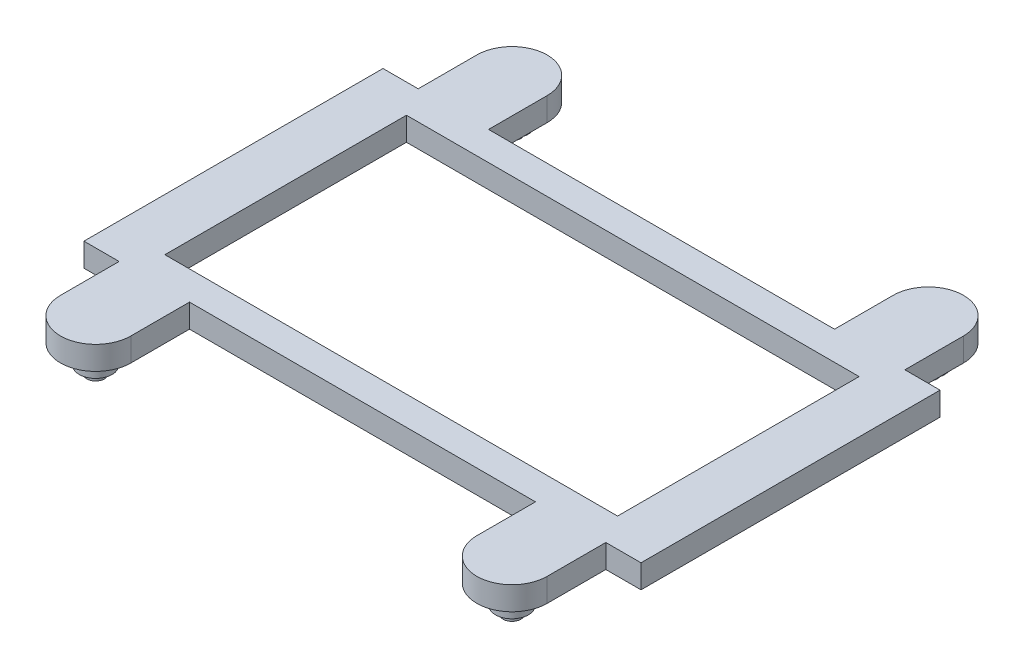
SolidWorks part; units mm, degrees
ref_plane "前视基准面" through (0, 0, 0) normal (0, 0, 1) x (1, 0, 0)
ref_plane "上视基准面" through (0, 0, 0) normal (0, 1, 0) x (1, 0, 0)
ref_plane "右视基准面" through (0, 0, 0) normal (1, 0, 0) x (0, 0, -1)
other "Configuration Table"
sketch "草图1" plane through (0, 0, 0) normal (0, 1, 0) x (1, 0, 0)
  line L0 (0, 35.4779) -> (0, -35.3561) construction
  line L1 (-47.5, 25.5) -> (-41.5, 25.5)
  line L2 (-47.5, 25.5) -> (-47.5, -25.5)
  line L3 (-47.5, -25.5) -> (-41.5, -25.5)
  line L4 (47.5, 25.5) -> (47.5, -25.5)
  line L5 (-47.5, 25.5) -> (47.5, -25.5) construction
  line L6 (-47.5, -25.5) -> (47.5, 25.5) construction
  line L9 (-41.5, 25.5) -> (-41.5, 35.5)
  line L11 (-29.5, 25.5) -> (-29.5, 35.5)
  line L12 (29.5, 25.5) -> (29.5, 35.5)
  line L14 (41.5, 25.5) -> (41.5, 35.5)
  line L15 (-78.7463, 0) -> (58.6748, 0) construction
  line L16 (41.5, -25.5) -> (41.5, -35.5)
  line L18 (29.5, -25.5) -> (29.5, -35.5)
  line L21 (-29.5, -25.5) -> (-29.5, -35.5)
  line L23 (-41.5, -25.5) -> (-41.5, -35.5)
  line L24 (-29.5, 25.5) -> (-3, 25.5)
  line L25 (41.5, 25.5) -> (47.5, 25.5)
  line L26 (41.5, -25.5) -> (47.5, -25.5)
  line L27 (-29.5, -25.5) -> (-3, -25.5)
  line L48 (3, 25.5) -> (29.5, 25.5)
  line L49 (3, -25.5) -> (29.5, -25.5)
  line L50 (-41.5, 35.5) -> (-29.5, 35.5) construction
  line L51 (-3, 25.5) -> (3, 25.5)
  line L52 (3, -25.5) -> (-3, -25.5)
  arc A16 (-29.5, 35.5) -> (-41.5, 35.5) centre (-35.5, 35.5) ccw
  arc A17 (29.5, 35.5) -> (41.5, 35.5) centre (35.5, 35.5) cw
  arc A18 (29.5, -35.5) -> (41.5, -35.5) centre (35.5, -35.5) ccw
  arc A19 (-29.5, -35.5) -> (-41.5, -35.5) centre (-35.5, -35.5) cw
  point P0 (0, 0)
  dimension "D10" = 71
  dimension "D1" = 95
  dimension "D3" = 83
  dimension "D4" = 12
  dimension "D5" = 10
extrude "凸台-拉伸1" add sketch "草图1" against normal blind 4
sketch "草图3" plane through (0, -4, 0) normal (0, -1, 0) x (1, 0, 0)
  line L0 (47.5, 25.5) -> (47.5, -25.5) construction
  line L1 (-45, -23) -> (45, -23)
  line L2 (-45, -23) -> (-45, 23)
  line L3 (-45, 23) -> (45, 23)
  line L4 (45, -23) -> (45, 23)
  line L5 (-45, -23) -> (45, 23) construction
  line L6 (-45, 23) -> (45, -23) construction
  line L7 (-29.5, 25.5) -> (29.5, 25.5) construction
  point P0 (0, 0)
  dimension "D1" = 2.5
  dimension "D2" = 2.5
sketch "草图4" plane through (0, -4, 0) normal (0, -1, 0) x (1, 0, 0)
  line L1 (-71.7869, 0) -> (71.1524, 0) construction
  line L2 (0, 61.1393) -> (0, -47.8922) construction
  circle A1 centre (35.5, 35.5) radius 2.8
  circle A2 centre (35.5, -35.5) radius 2.8
  circle A3 centre (-35.5, -35.5) radius 2.8
  circle A4 centre (-35.5, 35.5) radius 2.8
extrude "凸台-拉伸2" add sketch "草图4" along normal blind 3.3 separate body
sketch "草图5" plane through (0, -7.3, 0) normal (0, -1, 0) x (1, 0, 0)
  line L0 (-58.868, 0) -> (56.1189, 0) construction
  line L1 (0, 46.5823) -> (0, -51.4835) construction
  circle A0 centre (-35.5, 35.5) radius 1.5
  circle A1 centre (35.5, 35.5) radius 1.5
  circle A2 centre (35.5, -35.5) radius 1.5
  circle A3 centre (-35.5, -35.5) radius 1.5
extrude "凸台-拉伸3" add sketch "草图5" along normal blind 1.3 separate body
sketch "草图6" plane through (0, -4, 0) normal (0, -1, 0) x (1, 0, 0)
  line L0 (-29.5, 25.5) -> (29.5, 25.5) construction
  line L1 (-47.5, 25.5) -> (47.5, 25.5)
  line L2 (-47.5, 25.5) -> (-47.5, -25.5)
  line L3 (-47.5, -25.5) -> (47.5, -25.5)
  line L4 (47.5, 25.5) -> (47.5, -25.5)
  line L5 (29.5, -25.5) -> (-29.5, -25.5) construction
sketch "草图10" plane through (0, 0, 0) normal (0, 1, 0) x (1, 0, 0)
  line L5 (38.6, 20.6) -> (-38.6, 20.6)
  line L6 (38.6, 20.6) -> (38.6, -20.6)
  line L7 (38.6, -20.6) -> (-38.6, -20.6)
  line L8 (-38.6, 20.6) -> (-38.6, -20.6)
  line L9 (38.6, 20.6) -> (-38.6, -20.6) construction
  line L10 (38.6, -20.6) -> (-38.6, 20.6) construction
  point P0 (0, 0)
  dimension "D1" = 77.2
  dimension "D2" = 41.2
extrude "切除-拉伸5" cut sketch "草图10" against normal through all
sketch "草图16" plane through (0, 0, 0) normal (0, 1, 0) x (1, 0, 0)
  line L0 (-10, 23.05) -> (10, 23.05) construction
  line L1 (-10, 24.3) -> (10, 24.3)
  line L2 (-10, 21.8) -> (10, 21.8)
  line L3 (-1000, 0) -> (49000, 0) construction
  line L4 (0, -1000) -> (0, 49000) construction
  line L5 (29.5, 25.5) -> (-29.5, 25.5) construction
  line L6 (-10, -23.05) -> (10, -23.05) construction
  line L7 (-10, -24.3) -> (10, -24.3)
  line L8 (-10, -21.8) -> (10, -21.8)
  line L9 (38.6, 20.6) -> (-38.6, 20.6) construction
  arc A0 (-10, 24.3) -> (-10, 21.8) centre (-10, 23.05) ccw
  arc A1 (10, 21.8) -> (10, 24.3) centre (10, 23.05) ccw
  arc A2 (-10, -24.3) -> (-10, -21.8) centre (-10, -23.05) cw
  arc A3 (10, -21.8) -> (10, -24.3) centre (10, -23.05) cw
  circle A4 centre (19.07, 23.05) radius 1.6
  circle A5 centre (42.42, 23.05) radius 1.6
  circle A6 centre (-42.42, 23.05) radius 1.6
  circle A7 centre (-19.07, 23.05) radius 1.6
  circle A8 centre (42.42, -23.05) radius 1.6
  circle A9 centre (19.07, -23.05) radius 1.6
  circle A10 centre (-19.07, -23.05) radius 1.6
  circle A11 centre (-42.42, -23.05) radius 1.6
  point P2 (0, 23.05)
  point P17 (0, -23.05)
  point P27 (0, 23.05)
  dimension "D4" = 3.2
  dimension "D5" = 3.2
  dimension "D1" = 2.5
  dimension "D2" = 20
  dimension "D3" = 2.45
  dimension "D6" = 2.45
  dimension "D7" = 2.45
  dimension "D8" = 23.35
  dimension "D9" = 9.07
sketch "草图14" plane through (0, -3, 0) normal (0, -1, 0) x (1, 0, 0)
  line L0 (4.73, 0) -> (-4.73, 0) construction
  line L1 (-42, 24) -> (-37, 24)
  line L2 (-42, 24) -> (-42, 20)
  line L3 (-42, 20) -> (-37, 20)
  line L4 (-37, 24) -> (-37, 20)
  line L5 (-42, 24) -> (-37, 20) construction
  line L6 (-42, 20) -> (-37, 24) construction
  line L7 (-42, -20) -> (-37, -20)
  line L8 (-37, -24) -> (-37, -20)
  line L9 (-42, -24) -> (-37, -24)
  line L10 (-42, -24) -> (-42, -20)
  line L11 (0, -4.73) -> (0, 4.73) construction
  line L12 (42, -24) -> (42, -20)
  line L13 (42, -24) -> (37, -24)
  line L14 (37, -24) -> (37, -20)
  line L15 (42, -20) -> (37, -20)
  line L16 (42, 20) -> (37, 20)
  line L17 (37, 24) -> (37, 20)
  line L18 (42, 24) -> (37, 24)
  line L19 (42, 24) -> (42, 20)
  point P0 (-39.5, 22)
  dimension "D1" = 22
  dimension "D2" = 5
  dimension "D3" = 4
sketch "草图15" plane through (0, -3, 0) normal (0, -1, 0) x (1, 0, 0)
  line L0 (-45, 23) -> (32, 23) construction
  line L1 (-41, 20) -> (41, 20)
  line L2 (-41, 20) -> (-41, 16)
  line L3 (-41, 16) -> (41, 16)
  line L4 (41, 20) -> (41, 16)
  line L5 (-41, 20) -> (41, 16) construction
  line L6 (-41, 16) -> (41, 20) construction
  line L7 (4.73, 0) -> (-4.73, 0) construction
  line L8 (-41, -16) -> (41, -16)
  line L9 (41, -20) -> (41, -16)
  line L10 (-41, -20) -> (41, -20)
  line L11 (-41, -20) -> (-41, -16)
  line L12 (0, -4.73) -> (0, 4.73) construction
  line L13 (-40.75, 10) -> (-38.25, 10)
  line L14 (-40.75, 10) -> (-40.75, -10)
  line L15 (-40.75, -10) -> (-38.25, -10)
  line L16 (-38.25, 10) -> (-38.25, -10)
  line L17 (-40.75, 10) -> (-38.25, -10) construction
  line L18 (-40.75, -10) -> (-38.25, 10) construction
  line L19 (40.75, -10) -> (38.25, -10)
  line L20 (38.25, 10) -> (38.25, -10)
  line L21 (40.75, 10) -> (38.25, 10)
  line L22 (40.75, 10) -> (40.75, -10)
  point P0 (0, 18)
  point P5 (-39.5, 0)
  dimension "D1" = 4
  dimension "D2" = 5
  dimension "D3" = 82
  dimension "D4" = 2.5
  dimension "D5" = 20
